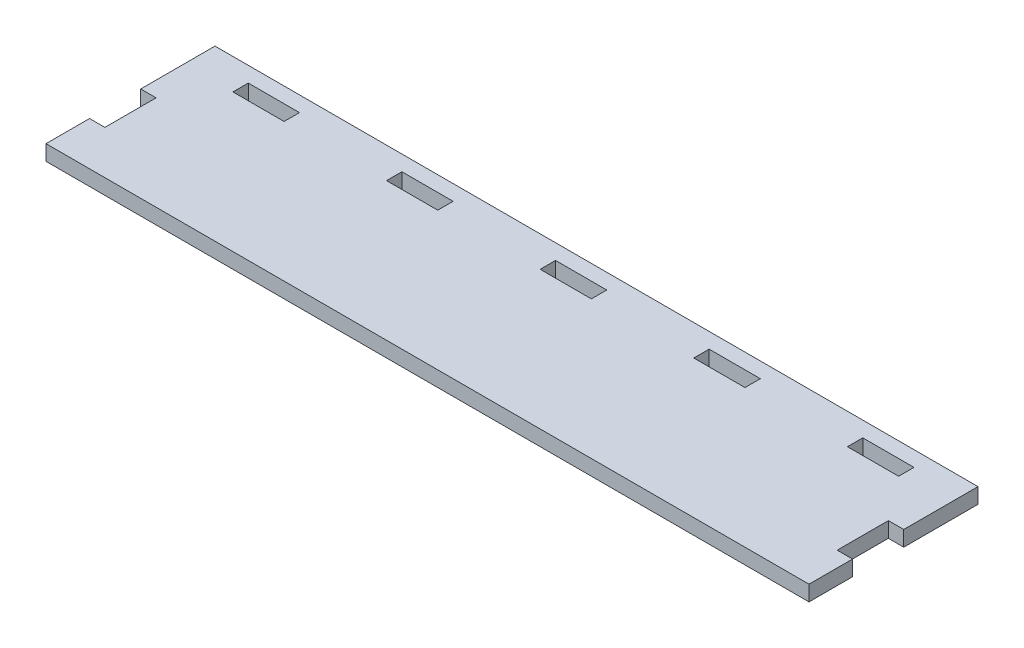
SolidWorks part; units mm, degrees
ref_plane "Front Plane" through (0, 0, 0) normal (0, 0, 1) x (1, 0, 0)
ref_plane "Top Plane" through (0, 0, 0) normal (0, 1, 0) x (1, 0, 0)
ref_plane "Right Plane" through (0, 0, 0) normal (1, 0, 0) x (0, 0, -1)
sketch "Sketch1" plane through (0, 0, 0) normal (0, 1, 0) x (1, 0, 0)
  line L0 (-55, 0) -> (55, 0) construction
  line L1 (-74.5, 0) -> (74.5, 0)
  line L2 (-74.5, 0) -> (-74.5, -14.5)
  line L3 (-74.5, -33) -> (74.5, -33)
  line L4 (74.5, 0) -> (74.5, -14.5)
  line L5 (0, -55) -> (0, 55) construction
  line L6 (-5, -3) -> (5, -3)
  line L7 (-5, -3) -> (-5, -6)
  line L8 (-5, -6) -> (5, -6)
  line L9 (5, -3) -> (5, -6)
  line L10 (25, -3) -> (35, -3)
  line L11 (25, -3) -> (25, -6)
  line L12 (25, -6) -> (35, -6)
  line L13 (35, -3) -> (35, -6)
  line L14 (55, -3) -> (65, -3)
  line L15 (55, -3) -> (55, -6)
  line L16 (55, -6) -> (65, -6)
  line L17 (65, -3) -> (65, -6)
  line L18 (-65, -3) -> (-65, -6)
  line L19 (-55, -6) -> (-65, -6)
  line L20 (-55, -3) -> (-55, -6)
  line L21 (-55, -3) -> (-65, -3)
  line L22 (-35, -3) -> (-35, -6)
  line L23 (-25, -6) -> (-35, -6)
  line L24 (-25, -3) -> (-25, -6)
  line L25 (-25, -3) -> (-35, -3)
  line L27 (71.5, -14.5) -> (74.5, -14.5)
  line L28 (71.5, -14.5) -> (71.5, -24.5)
  line L29 (71.5, -24.5) -> (74.5, -24.5)
  line L31 (-71.5, -24.5) -> (-74.5, -24.5)
  line L32 (-71.5, -14.5) -> (-71.5, -24.5)
  line L33 (-71.5, -14.5) -> (-74.5, -14.5)
  line L34 (-74.5, -24.5) -> (-74.5, -33)
  line L35 (74.5, -24.5) -> (74.5, -33)
  point P6 (0, 0)
  point P12 (0, -3)
  dimension "D1" = 33
  dimension "D2" = 149
  dimension "D3" = 3
  dimension "D4" = 3
  dimension "D5" = 10
  dimension "D7" = 3
  dimension "D8" = 10
  dimension "D9" = 8.5
  dimension "D10" = 20
  dimension "D6" = 3
extrude "Boss-Extrude1" add sketch "Sketch1" along normal blind 3
